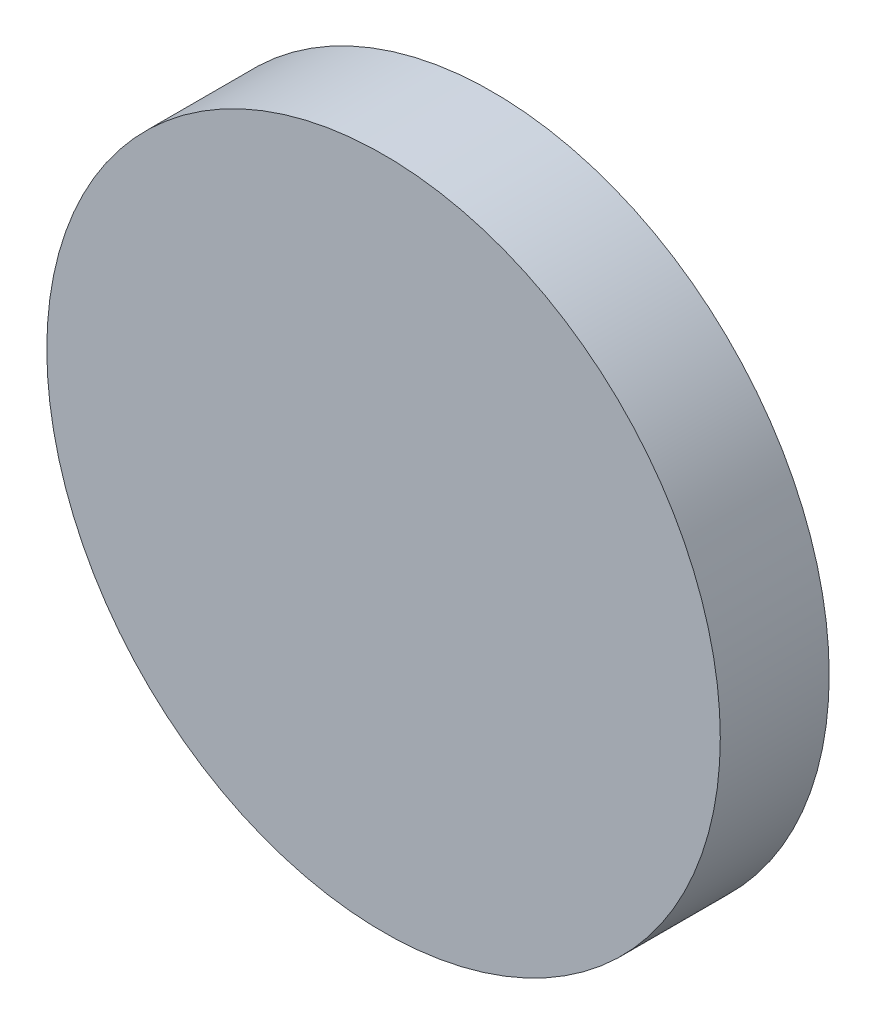
SolidWorks part; units mm, degrees
ref_plane "Front Plane" through (0, 0, 0) normal (0, 0, 1) x (1, 0, 0)
ref_plane "Top Plane" through (0, 0, 0) normal (0, 1, 0) x (1, 0, 0)
ref_plane "Right Plane" through (0, 0, 0) normal (1, 0, 0) x (0, 0, -1)
other "Configuration Table"
sketch "Sketch1" plane through (0, 0, 0) normal (0, 0, 1) x (1, 0, 0)
  circle A0 centre (0, 0) radius 47.9141
extrude "Boss-Extrude1" add sketch "Sketch1" along normal blind 15.494
